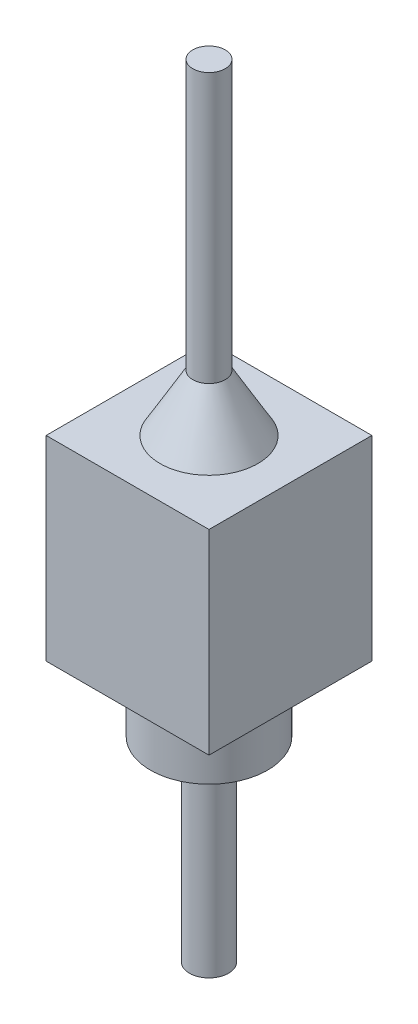
SolidWorks part; units mm, degrees
ref_plane "Спереди" through (0, 0, 0) normal (0, 0, 1) x (1, 0, 0)
ref_plane "Сверху" through (0, 0, 0) normal (0, 1, 0) x (1, 0, 0)
ref_plane "Справа" through (0, 0, 0) normal (1, 0, 0) x (0, 0, -1)
sketch "Эскиз1" plane through (0, 0, 0) normal (0, 1, 0) x (1, 0, 0)
  line L1 (1.25, 1.25) -> (-1.25, 1.25)
  line L2 (1.25, 1.25) -> (1.25, -1.25)
  line L3 (1.25, -1.25) -> (-1.25, -1.25)
  line L4 (-1.25, 1.25) -> (-1.25, -1.25)
  line L5 (1.25, 1.25) -> (-1.25, -1.25) construction
  line L6 (1.25, -1.25) -> (-1.25, 1.25) construction
  point P0 (0, 0)
  dimension "D1" = 2.5
extrude "Бобышка-Вытянуть1" add sketch "Эскиз1" along normal blind 3
sketch "Эскиз3" plane through (0, 0, 0) normal (0, -1, 0) x (1, 0, 0)
  circle A0 centre (0, 0) radius 0.9
  dimension "D1" = 1.8
extrude "Бобышка-Вытянуть2" add sketch "Эскиз3" along normal blind 1
sketch "Эскиз4" plane through (0, -1, 0) normal (0, -1, 0) x (1, 0, 0)
  circle A0 centre (0, 0) radius 0.3
  dimension "D1" = 0.6
extrude "Бобышка-Вытянуть3" add sketch "Эскиз4" along normal blind 3
sketch "Эскиз5" plane through (0, 3, 0) normal (0, 1, 0) x (1, 0, 0)
  circle A0 centre (0, 0) radius 0.25
  dimension "D1" = 0.5
extrude "Бобышка-Вытянуть4" add sketch "Эскиз5" along normal blind 5
chamfer "Фаска1" distance 0.5 angle 60 1 edges at (0, 3, -0.25)
